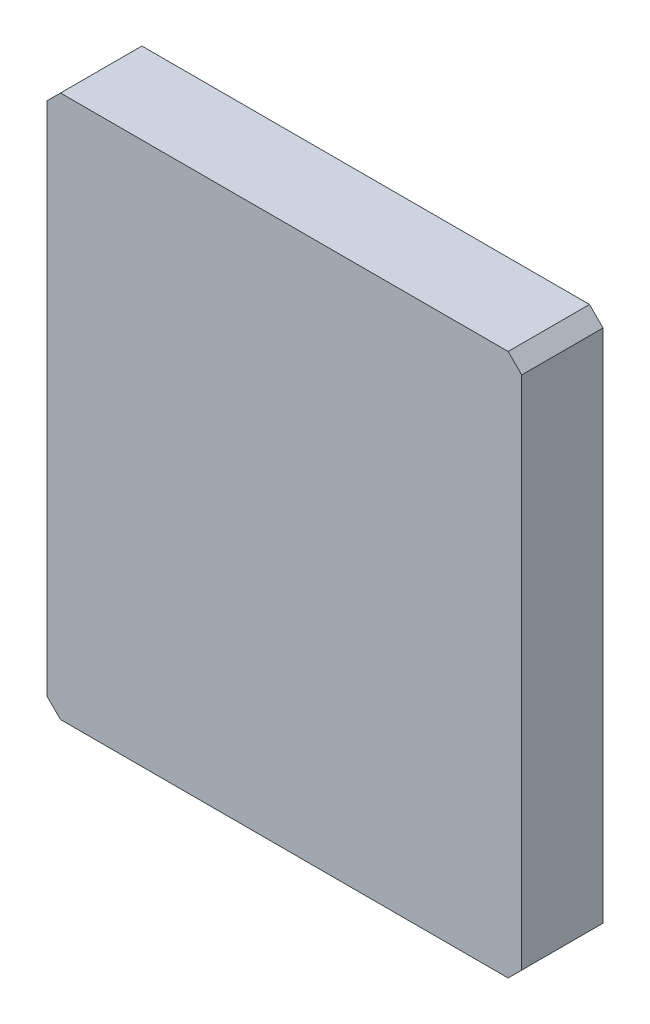
SolidWorks part; units mm, degrees
ref_plane "Piano frontale" through (0, 0, 0) normal (0, 0, 1) x (1, 0, 0)
ref_plane "Piano superiore" through (0, 0, 0) normal (0, 1, 0) x (1, 0, 0)
ref_plane "Piano destro" through (0, 0, 0) normal (1, 0, 0) x (0, 0, -1)
sketch "Schizzo1" plane through (0, 0, 0) normal (0, 0, 1) x (1, 0, 0)
  line L1 (-8.75, 10) -> (8.75, 10)
  line L2 (-8.75, 10) -> (-8.75, -10)
  line L3 (-8.75, -10) -> (8.75, -10)
  line L4 (8.75, 10) -> (8.75, -10)
  line L5 (-8.75, 10) -> (8.75, -10) construction
  line L6 (-8.75, -10) -> (8.75, 10) construction
  point P0 (0, 0)
  point P5 (0, 0)
  point P7 (0, 0)
  point P8 (0, 0)
  dimension "D1" = 17.5
  dimension "D2" = 20
extrude "Estrusione-Estrusione1" add sketch "Schizzo1" against normal blind 3
chamfer "Smusso1" distance 0.5 angle 45 1 edges at (-8.75, -10, -1.5)
chamfer "Smusso2" distance 0.5 angle 45 1 edges at (8.75, -10, -1.5)
chamfer "Smusso3" distance 0.5 angle 45 1 edges at (8.75, 10, -1.5)
chamfer "Smusso4" distance 0.5 angle 45 1 edges at (-8.75, 10, -1.5)
